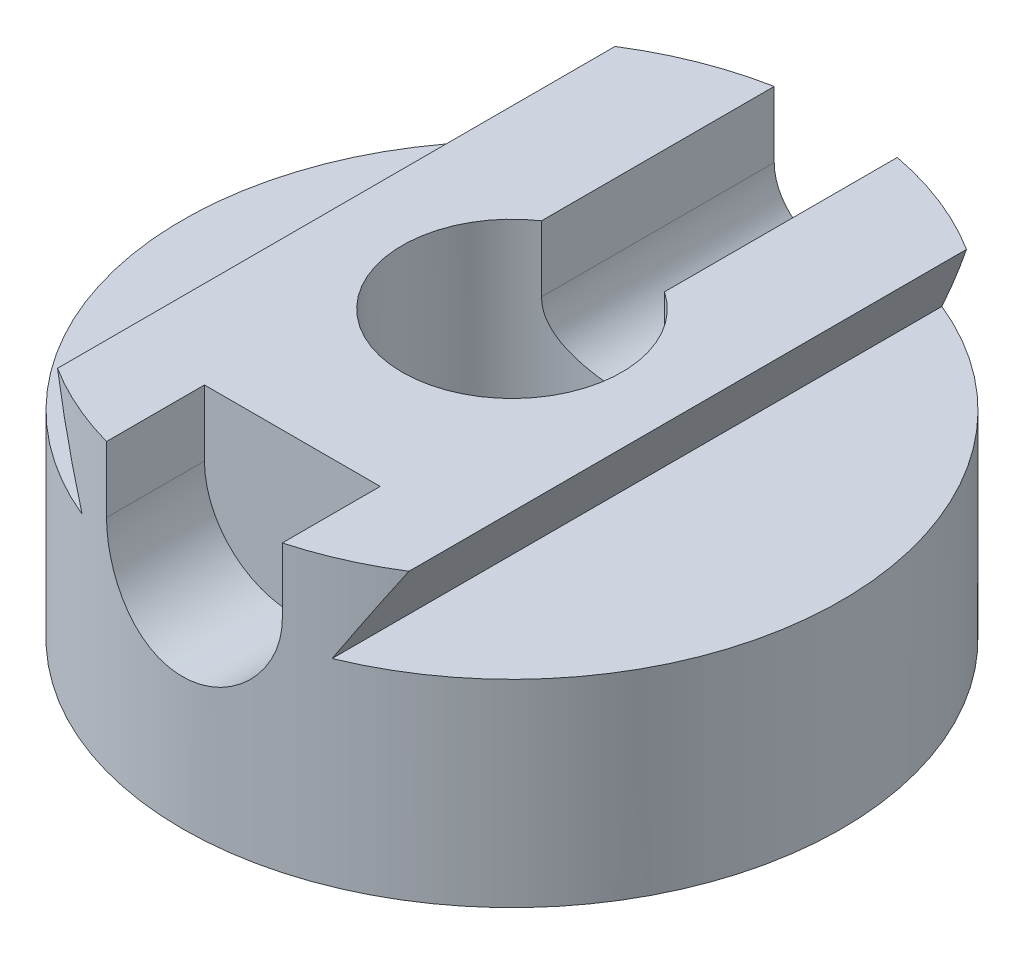
SolidWorks part; units mm, degrees
ref_plane "Front Plane" through (0, 0, 0) normal (0, 0, 1) x (1, 0, 0)
ref_plane "Top Plane" through (0, 0, 0) normal (0, 1, 0) x (1, 0, 0)
ref_plane "Right Plane" through (0, 0, 0) normal (1, 0, 0) x (0, 0, -1)
sketch "Sketch2" plane through (0, 0, 0) normal (0, 1, 0) x (1, 0, 0)
  circle A0 centre (0, 0) radius 75
  circle A1 centre (0, 0) radius 12.5
  dimension "D1" = 150
  dimension "D2" = 25
extrude "Boss-Extrude1" add sketch "Sketch2" along normal blind 65
sketch "Sketch3" plane through (0, 0, 0) normal (0, 0, 1) x (1, 0, 0)
  line L1 (12.5, 65) -> (-12.5, 65) construction
  line L2 (-14, 50) -> (-14, 77.8524)
  line L3 (-14, 77.8524) -> (14, 77.8524)
  line L4 (14, 77.8524) -> (14, 50)
  circle A0 centre (0, 50) radius 14
  dimension "D1" = 28
  dimension "D2" = 15
extrude "Cut-Extrude1" cut sketch "Sketch3" against normal blind 89 contours A0 L4 L3 L2 | A0
sketch "Sketch4" plane through (0, 65, 0) normal (0, 1, 0) x (1, 0, 0)
  circle A0 centre (0, 0) radius 25
extrude "Cut-Extrude2" cut sketch "Sketch4" against normal blind 40
sketch "Sketch5" plane through (0, 0, 0) normal (0, 0, 1) x (1, 0, 0)
  line L0 (-75, 65) -> (-40, 65)
  line L1 (75, 65) -> (-75, 65) construction
  line L2 (-40, 65) -> (-28.453, 45)
  line L3 (-28.453, 45) -> (-75, 45)
  line L4 (-75, 65) -> (-75, 0) construction
  line L5 (-75, 45) -> (-75, 65)
  line L6 (0, 0) -> (0, 65) construction
  line L7 (75, 65) -> (40, 65)
  line L8 (75, 45) -> (75, 65)
  line L9 (28.453, 45) -> (75, 45)
  line L10 (40, 65) -> (28.453, 45)
  dimension "D1" = 20
  dimension "D2" = 35
  dimension "D3" = 60
extrude "Cut-Extrude3" cut sketch "Sketch5" against normal mid plane 195
ref_plane "NEW" through (0, 0, 50) normal (0, 0, 1) x (1, 0, 0)
sketch "Sketch7" plane through (0, 0, 50) normal (0, 0, 1) x (1, 0, 0)
  line L0 (-20, 50) -> (-20, 82.2123)
  line L1 (-20, 82.2123) -> (20, 82.2123)
  line L2 (20, 82.2123) -> (20, 50)
  circle A0 centre (0, 50) radius 20
  dimension "D1" = 40
extrude "Cut-Extrude4" cut sketch "Sketch7" along normal blind 73 contours A0 | A0 L2 L1 L0
